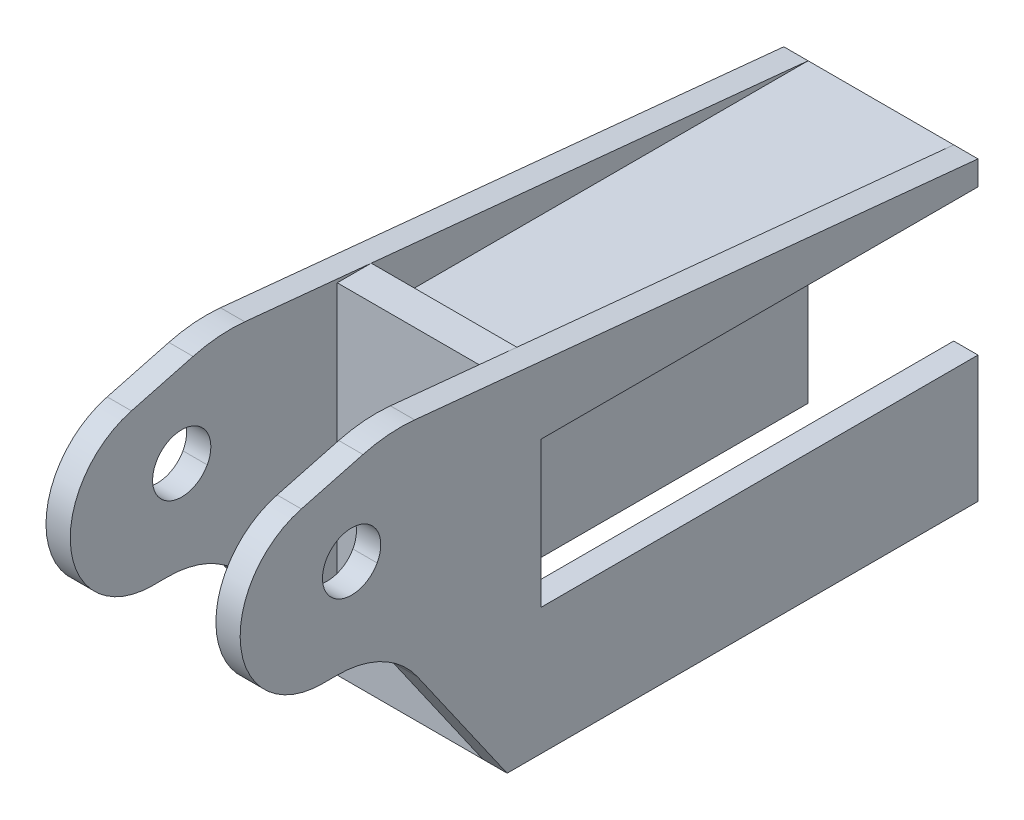
SolidWorks part; units mm, degrees
ref_plane "Płaszczyzna przednia" through (0, 0, 0) normal (0, 0, 1) x (1, 0, 0)
ref_plane "Płaszczyzna górna" through (0, 0, 0) normal (0, 1, 0) x (1, 0, 0)
ref_plane "Płaszczyzna prawa" through (0, 0, 0) normal (1, 0, 0) x (0, 0, -1)
sketch "Szkic1" plane through (0, 0, 0) normal (0, 0, 1) x (1, 0, 0)
  line L1 (-15, -35) -> (15, -35)
  line L2 (-15, -35) -> (-15, 35)
  line L3 (-15, 35) -> (15, 35)
  line L4 (15, -35) -> (15, 35)
  line L5 (-15, -35) -> (15, 35) construction
  line L6 (-15, 35) -> (15, -35) construction
  point P0 (0, 0)
  dimension "D1" = 30
  dimension "D2" = 70
extrude "Dodanie-wyciągnięcie1" add sketch "Szkic1" along normal blind 7
sketch "Szkic5" plane through (-15, 0, 0) normal (-1, 0, 0) x (0, 0, 1)
  line L0 (7, -35) -> (31.4522, 0)
  line L1 (31.4522, 0) -> (62, 0)
  line L2 (62, 0) -> (62, 30)
  line L3 (62, 30) -> (31.4522, 38.1068)
  line L4 (31.4522, 38.1068) -> (0, 35)
  line L6 (-90, 21.11) -> (0, 21.11)
  line L7 (0, 35) -> (0, -35) construction
  line L8 (0, 21.11) -> (0, -35)
  line L9 (0, -35) -> (7, -35)
  line L10 (7, 35) -> (7, -35) construction
  line L11 (-90, 21.11) -> (-90, 26.11)
  line L12 (-90, 26.11) -> (0, 35)
  dimension "D1" = 90
  dimension "D2" = 13.89
  dimension "D3" = 55
  dimension "D4" = 30
  dimension "D5" = 70
  dimension "D6" = 5
extrude "Dodanie-wyciągnięcie2" add sketch "Szkic5" along normal blind 5
mirror "Lustro1" about plane through (0, 0, 0) normal (1, 0, 0) of "Dodanie-wyciągnięcie2"
fillet "Zaokrąglenie1" radius 16.9565 4 edges at (-15, 15, 62) (-17.5, 0, 62) (-17.5, 30, 62) (-20, 15, 62)
fillet "Zaokrąglenie2" radius 16.9565 4 edges at (20, 15, 62) (17.5, 30, 62) (17.5, 0, 62) (15, 15, 62)
fillet "Zaokrąglenie3" radius 30 1 edges at (-17.5, 38.1068, 31.4522)
fillet "Zaokrąglenie4" radius 30 1 edges at (17.5, 38.1068, 31.4522)
fillet "Zaokrąglenie5" radius 20 1 edges at (-17.5, 0, 31.4522)
fillet "Zaokrąglenie6" radius 20 1 edges at (17.5, 0, 31.4522)
sketch "Szkic6" plane through (-20, 0, 0) normal (-1, 0, 0) x (0, 0, 1)
  line L0 (0, 21.11) -> (0, -35) construction
  line L1 (-90, 21.11) -> (0, 21.11) construction
  circle A0 centre (39.04, 18.8) radius 6
  dimension "D1" = 12
  dimension "D2" = 39.04
  dimension "D3" = 2.31
extrude "Wytnij-wyciągnięcie2" cut sketch "Szkic6" against normal through all contours A0
sketch "Szkic7" plane through (-20, 0, 0) normal (-1, 0, 0) x (0, 0, 1)
  line L0 (39.04, 18.8) -> (39.04, -197.59)
  line L1 (39.04, -197.59) -> (158, -197.59)
  line L2 (158, -197.59) -> (39.04, 18.8)
ref_plane "Płaszczyzna1" through (-20, -197.59, 158) normal (0, 0.8763, -0.4817) x (1, 0, 0)
sketch "Szkic8" plane through (-20, -197.59, 158) normal (0, 0.8763, -0.4817) x (1, 0, 0)
  line L0 (0, 3.796) -> (0, -21.3293) construction
  line L1 (5, 6) -> (0, 6)
  line L2 (5, 6) -> (5, -6)
  line L3 (5, -6) -> (0, -6)
  line L4 (0, 6) -> (0, -6)
  line L5 (5, 6) -> (0, -6) construction
  line L6 (5, -6) -> (0, 6) construction
  line L7 (5, -21.3293) -> (5, 3.796) construction
  line L8 (20, 39.418) -> (20, 47.118) construction
  line L9 (35, -6) -> (40, 6) construction
  line L10 (35, 6) -> (40, -6) construction
  line L11 (40, 6) -> (40, -6)
  line L12 (35, -6) -> (40, -6)
  line L13 (35, 6) -> (35, -6)
  line L14 (35, 6) -> (40, 6)
  point P0 (2.5, 0)
  point P17 (37.5, 0)
  dimension "D1" = 12
split line "Linia podziałowa1"
sketch "Szkic9" plane through (0, 0, 0) normal (0, 0, -1) x (-1, 0, 0)
  line L0 (20, -35) -> (-20, -35) construction
  line L1 (-15, -8.89) -> (-20, -8.89)
  line L2 (-15, -8.89) -> (-15, -35)
  line L3 (-15, -35) -> (-20, -35)
  line L4 (-20, -8.89) -> (-20, -35)
  line L5 (-15, 21.11) -> (-15, 35) construction
  line L6 (15, -8.89) -> (20, -8.89)
  line L7 (15, -8.89) -> (15, -35)
  line L8 (15, -35) -> (20, -35)
  line L9 (20, -8.89) -> (20, -35)
  line L10 (15, 35) -> (15, 21.11) construction
  line L11 (-20, 21.11) -> (-15, 21.11) construction
  line L12 (-20, 21.11) -> (-20, -35) construction
  line L13 (20, 21.11) -> (20, -35) construction
  dimension "D1" = 30
extrude "Dodanie-wyciągnięcie3" add sketch "Szkic9" along normal up to surface (90 mm away) up to face at (17.5, 23.61, -90)
sketch "Szkic10" plane through (20, 0, 0) normal (1, 0, 0) x (0, 0, -1)
  line L4 (0, -8.89) -> (0, 21.11)
  line L5 (-7, -35) -> (90, -35)
  line L6 (90, -35) -> (90, -8.89)
  line L7 (90, -8.89) -> (0, -8.89)
  line L9 (-7, -35) -> (90, -35)
  line L10 (90, -35) -> (90, -8.89)
  line L11 (90, -8.89) -> (0, -8.89)
  line L19 (0, -8.89) -> (0, 21.11)
  line L20 (90, 26.11) -> (-26.0525, 37.5734)
  line L21 (90, 26.11) -> (-26.0525, 37.5734)
  line L22 (-36.6965, 36.715) -> (-49.3929, 33.3457)
  line L23 (-36.6965, 36.715) -> (-49.3929, 33.3457)
  line L24 (-45.0435, 0) -> (-41.8769, 0)
  line L25 (-45.0435, 0) -> (-41.8769, 0)
  line L26 (-25.4818, -8.5458) -> (-7, -35)
  line L27 (-25.4818, -8.5458) -> (-7, -35)
  line L28 (0, 21.11) -> (90, 21.11)
  line L29 (0, 21.11) -> (90, 21.11)
  line L30 (90, 21.11) -> (90, 26.11)
  line L31 (90, 21.11) -> (90, 26.11)
  arc A3 (-26.0525, 37.5734) -> (-36.6965, 36.715) centre (-29.0015, 7.7187) ccw
  arc A4 (-26.0525, 37.5734) -> (-36.6965, 36.715) centre (-29.0015, 7.7187) ccw
  arc A5 (-49.3929, 33.3457) -> (-45.0435, 0) centre (-45.0435, 16.9565) ccw
  arc A6 (-49.3929, 33.3457) -> (-45.0435, 0) centre (-45.0435, 16.9565) ccw
  arc A7 (-25.4818, -8.5458) -> (-41.8769, 0) centre (-41.8769, -20) ccw
  arc A8 (-25.4818, -8.5458) -> (-41.8769, 0) centre (-41.8769, -20) ccw
  dimension "D1" = 0
sketch "Szkic11" plane through (-20, 0, 0) normal (-1, 0, 0) x (0, 0, 1)
  line L4 (0, 21.11) -> (0, -8.89)
  line L5 (0, -8.89) -> (-90, -8.89)
  line L6 (-90, -8.89) -> (-90, -35)
  line L7 (-90, -35) -> (7, -35)
  line L9 (0, -8.89) -> (-90, -8.89)
  line L10 (-90, -8.89) -> (-90, -35)
  line L11 (-90, -35) -> (7, -35)
  line L19 (0, 21.11) -> (0, -8.89)
  line L20 (41.8769, 0) -> (45.0435, 0)
  line L21 (41.8769, 0) -> (45.0435, 0)
  line L22 (49.3929, 33.3457) -> (36.6965, 36.715)
  line L23 (49.3929, 33.3457) -> (36.6965, 36.715)
  line L24 (26.0525, 37.5734) -> (-90, 26.11)
  line L25 (26.0525, 37.5734) -> (-90, 26.11)
  line L26 (-90, 26.11) -> (-90, 21.11)
  line L27 (-90, 26.11) -> (-90, 21.11)
  line L28 (-90, 21.11) -> (0, 21.11)
  line L29 (-90, 21.11) -> (0, 21.11)
  line L30 (7, -35) -> (25.4818, -8.5458)
  line L31 (7, -35) -> (25.4818, -8.5458)
  arc A3 (41.8769, 0) -> (25.4818, -8.5458) centre (41.8769, -20) ccw
  arc A4 (41.8769, 0) -> (25.4818, -8.5458) centre (41.8769, -20) ccw
  arc A5 (45.0435, 0) -> (49.3929, 33.3457) centre (45.0435, 16.9565) ccw
  arc A6 (45.0435, 0) -> (49.3929, 33.3457) centre (45.0435, 16.9565) ccw
  arc A7 (36.6965, 36.715) -> (26.0525, 37.5734) centre (29.0015, 7.7187) ccw
  arc A8 (36.6965, 36.715) -> (26.0525, 37.5734) centre (29.0015, 7.7187) ccw
  dimension "D1" = 0
ref_plane "Płaszczyzna2" through (15, 21.11, 0) normal (0, 1, 0) x (1, 0, 0)
sketch "Szkic13" plane through (0, 21.11, 0) normal (0, -1, 0) x (1, 0, 0)
  line L1 (15, 0) -> (-15, 0)
  line L2 (15, 0) -> (15, -90)
  line L3 (15, -90) -> (-15, -90)
  line L4 (-15, 0) -> (-15, -90)
extrude "Dodanie-wyciągnięcie6" add sketch "Szkic13" against normal up to vertex (5 mm away) contours L3 L4 L1 L2 up to point (-15, 26.11, -90)
extrude "Wytnij-wyciągnięcie4" cut sketch "Szkic15" against normal blind 50
sketch "Szkic15" plane through (-20, -323.89, -399) normal (-1, 0, 0) x (0, 0, 1)
  circle A0 centre (432.3836, 321.3555) radius 6
